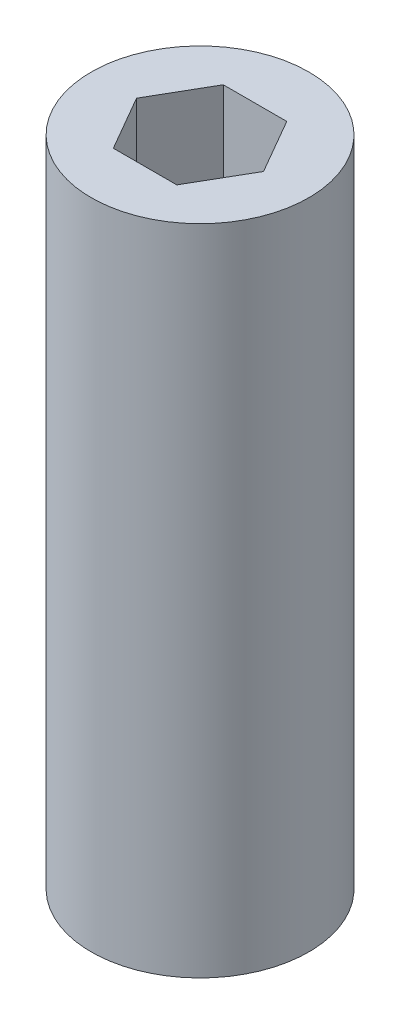
SolidWorks part; units mm, degrees
ref_plane "Front Plane" through (0, 0, 0) normal (0, 0, 1) x (1, 0, 0)
ref_plane "Top Plane" through (0, 0, 0) normal (0, 1, 0) x (1, 0, 0)
ref_plane "Right Plane" through (0, 0, 0) normal (1, 0, 0) x (0, 0, -1)
sketch "Sketch1" plane through (0, 0, 0) normal (0, 1, 0) x (1, 0, 0)
  circle A0 centre (0, 0) radius 12.7
  dimension "D1" = 25.4
extrude "Boss-Extrude1" add sketch "Sketch1" along normal blind 76.2
sketch "Sketch2" plane through (0, 76.2, 0) normal (0, 1, 0) x (1, 0, 0)
  circle A0 centre (0, 0) radius 12.7
extrude "Boss-Extrude2" [suppressed] add sketch "Sketch2" against normal blind 50.8 draft 5
sketch "Sketch3" plane through (0, 0, 0) normal (0, -1, 0) x (-1, 0, 0)
  circle A0 centre (0, 0) radius 12.7
extrude "Boss-Extrude3" [suppressed] add sketch "Sketch3" against normal blind 50.8 draft 5
sketch "Sketch5" plane through (0, 0, 0) normal (0, -1, 0) x (-1, 0, 0)
  line L1 (-7.4057, 0) -> (-3.7028, -6.4135)
  line L2 (-3.7028, -6.4135) -> (3.7028, -6.4135)
  line L3 (3.7028, -6.4135) -> (7.4057, 0)
  line L4 (7.4057, 0) -> (3.7028, 6.4135)
  line L5 (3.7028, 6.4135) -> (-3.7028, 6.4135)
  line L6 (-3.7028, 6.4135) -> (-7.4057, 0)
  circle A0 centre (0, 0) radius 6.4135 construction
  dimension "D1" = 12.827
extrude "Cut-Extrude1" cut sketch "Sketch5" against normal through all
